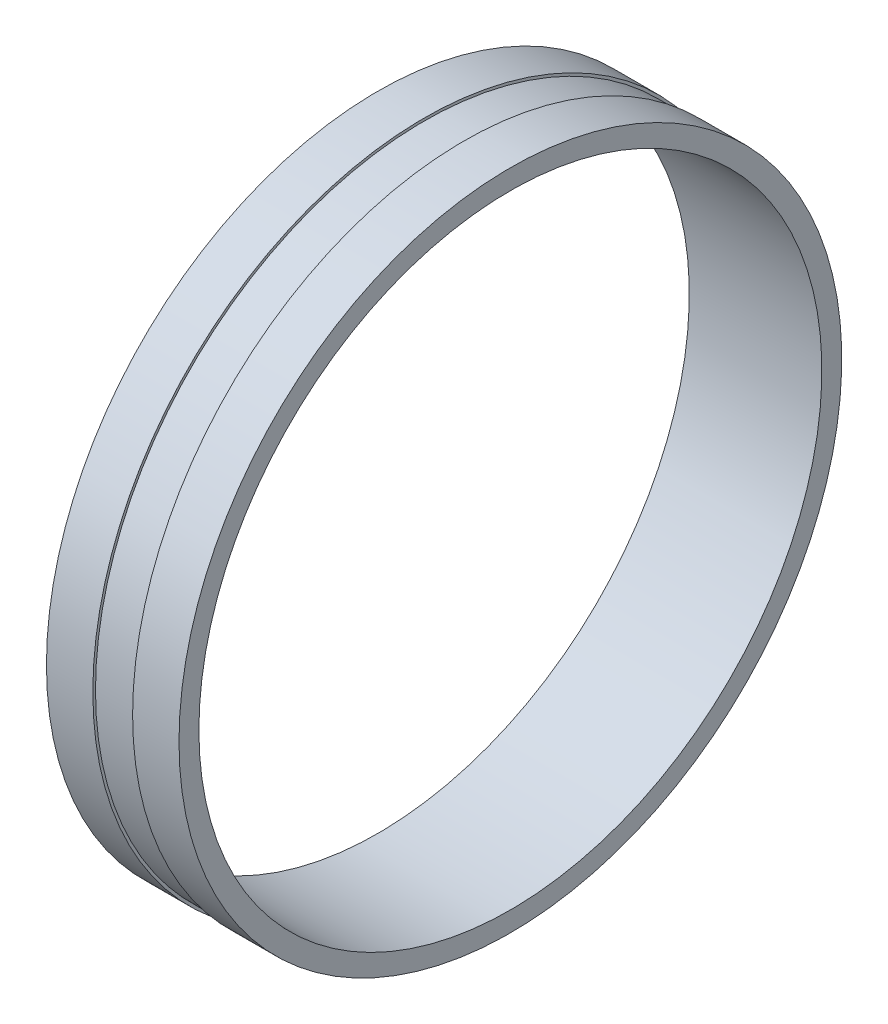
SolidWorks part; units mm, degrees
ref_plane "Płaszczyzna przednia" through (0, 0, 0) normal (0, 0, 1) x (1, 0, 0)
ref_plane "Płaszczyzna górna" through (0, 0, 0) normal (0, 1, 0) x (1, 0, 0)
ref_plane "Płaszczyzna prawa" through (0, 0, 0) normal (1, 0, 0) x (0, 0, -1)
sketch "Szkic2" plane through (0, 0, 0) normal (0, 0, 1) x (1, 0, 0)
  line L0 (-420.5378, -179.4486) -> (-420.5378, 37.7167) construction
  line L1 (-425.5378, -177.9486) -> (-422.0378, -177.9486)
  line L2 (-425.5378, -177.9486) -> (-425.5378, -179.4486)
  line L3 (-425.5378, -179.4486) -> (-415.5378, -179.4486)
  line L4 (-415.5378, -177.9486) -> (-415.5378, -179.4486)
  line L5 (-422.0378, -177.9486) -> (-422.0378, -178.1486)
  line L6 (-422.0378, -178.1486) -> (-419.0378, -178.1486)
  line L7 (-419.0378, -177.9486) -> (-419.0378, -178.1486)
  line L8 (-419.0378, -177.9486) -> (-415.5378, -177.9486)
  line L9 (-411.4991, -202.9486) -> (27.8694, -202.9486) construction
  point P12 (-420.5378, -178.1486)
  dimension "D1" = 3
  dimension "D2" = 0.2
  dimension "D3" = 10
  dimension "D4" = 1.5
  dimension "D5" = 47
revolve "Obrót1" add sketch "Szkic2" angle 360 about L9
